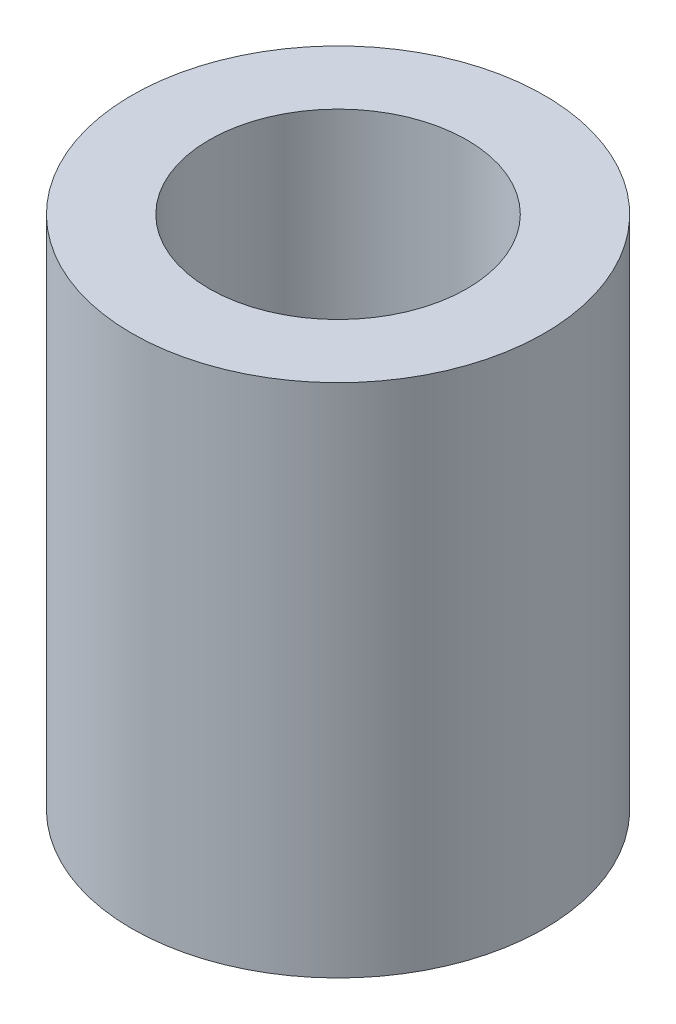
SolidWorks part; units mm, degrees
ref_plane "Front" through (0, 0, 0) normal (0, 0, 1) x (1, 0, 0)
ref_plane "Top" through (0, 0, 0) normal (0, 1, 0) x (1, 0, 0)
ref_plane "Right" through (0, 0, 0) normal (1, 0, 0) x (0, 0, -1)
sketch "Sketch1" plane through (0, 0, 0) normal (0, 1, 0) x (1, 0, 0)
  circle A0 centre (0, 0) radius 4
  circle A1 centre (0, 0) radius 2.5
  dimension "D1" = 8
  dimension "D2" = 5
extrude "Boss-Extrude1" add sketch "Sketch1" along normal mid plane 10
